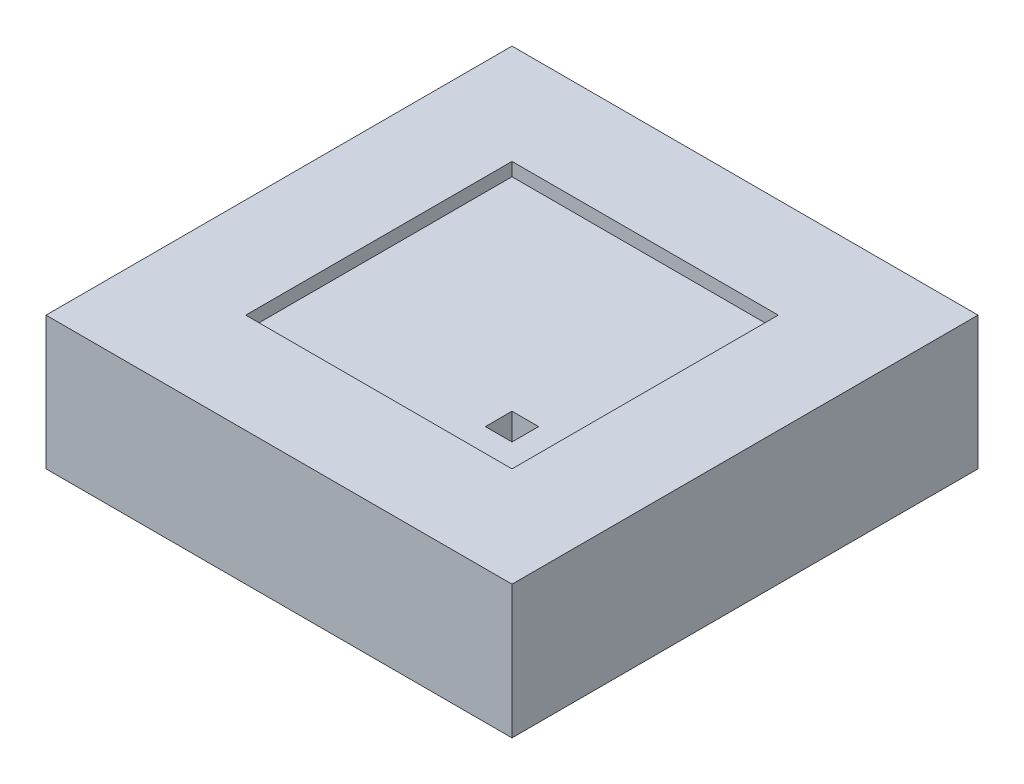
SolidWorks part; units mm, degrees
ref_plane "Alzado" through (0, 0, 0) normal (0, 0, 1) x (1, 0, 0)
ref_plane "Planta" through (0, 0, 0) normal (0, 1, 0) x (1, 0, 0)
ref_plane "Vista lateral" through (0, 0, 0) normal (1, 0, 0) x (0, 0, -1)
sketch "Croquis1" plane through (0, 0, 0) normal (0, 1, 0) x (1, 0, 0)
  line L1 (0, 0) -> (70, 0)
  line L2 (0, 0) -> (0, 70)
  line L3 (0, 70) -> (70, 70)
  line L4 (70, 0) -> (70, 70)
  dimension "D1" = 70
extrude "Saliente-Extruir1" add sketch "Croquis1" along normal blind 20
sketch "Croquis2" plane through (0, 20, 0) normal (0, 1, 0) x (1, 0, 0)
  line L8 (15, 55) -> (15, 15)
  line L9 (15, 15) -> (55, 15)
  line L10 (55, 15) -> (55, 55)
  line L11 (55, 55) -> (15, 55)
  line L12 (15, 55) -> (15, 15)
  line L13 (15, 15) -> (55, 15)
  line L14 (55, 15) -> (55, 55)
  line L15 (55, 55) -> (15, 55)
  dimension "D1" = 15
extrude "Cortar-Extruir1" cut sketch "Croquis2" against normal blind 2
sketch "Croquis3" plane through (0, 18, 0) normal (0, 1, 0) x (1, 0, 0)
  line L0 (55, 15) -> (55, 55) construction
  line L1 (45.5, 20.5) -> (49.5, 20.5)
  line L2 (45.5, 20.5) -> (45.5, 24.5)
  line L3 (45.5, 24.5) -> (49.5, 24.5)
  line L4 (49.5, 20.5) -> (49.5, 24.5)
  line L5 (15, 15) -> (55, 15) construction
  dimension "D1" = 4
  dimension "D2" = 5.5
  dimension "D3" = 5.5
extrude "Cortar-Extruir2" cut sketch "Croquis3" against normal blind 55
